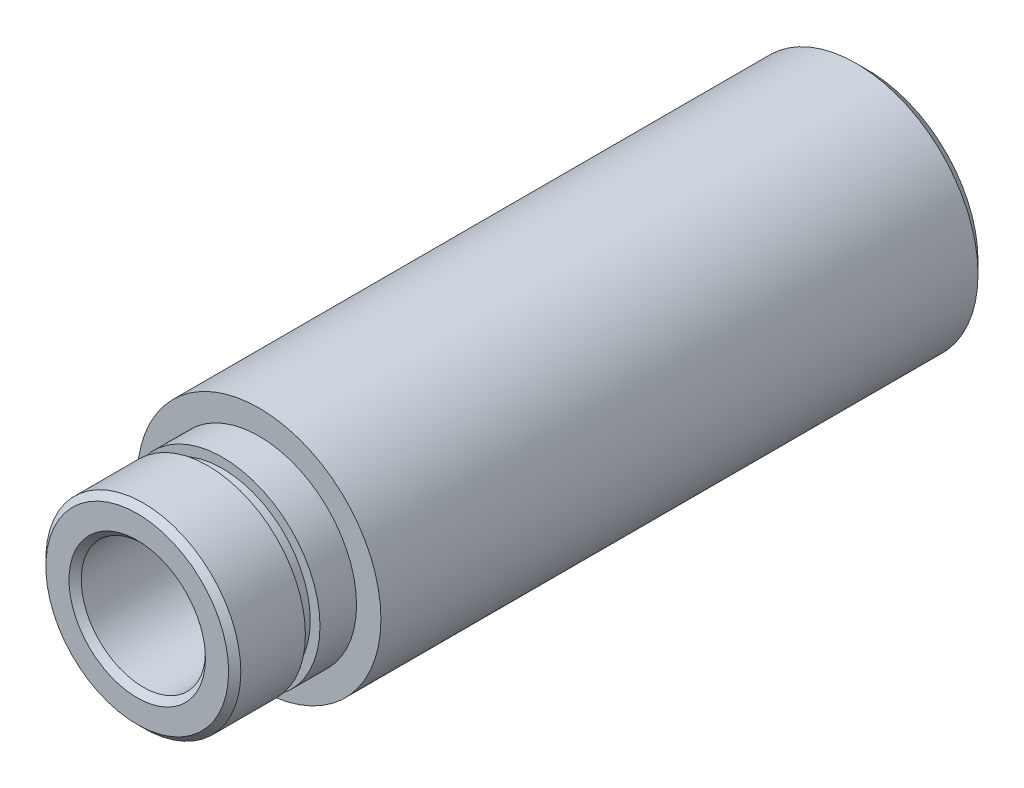
SolidWorks part; units mm, degrees
ref_plane "Alzado" through (0, 0, 0) normal (0, 0, 1) x (1, 0, 0)
ref_plane "Planta" through (0, 0, 0) normal (0, 1, 0) x (1, 0, 0)
ref_plane "Vista lateral" through (0, 0, 0) normal (1, 0, 0) x (0, 0, -1)
sketch "Croquis1" plane through (0, 0, 0) normal (0, 0, 1) x (1, 0, 0)
  circle A0 centre (0, 0) radius 5.1
  circle A1 centre (0, 0) radius 10
  dimension "D1" = 10.2
  dimension "D2" = 20
extrude "Saliente-Extruir1" add sketch "Croquis1" along normal mid plane 60
sketch "Croquis2" plane through (0, 0, 30) normal (0, 0, 1) x (1, 0, 0)
  circle A0 centre (0, 0) radius 8
  dimension "D1" = 16
extrude "Cortar-Extruir1" cut sketch "Croquis2" against normal blind 10 flip side to cut
chamfer "Chaflán1" distance 0.5 angle 45 3 edges at (5.1, 0, -30) (5.1, 0, 30) (8, 0, 30)
sketch "Croquis3" plane through (0, 0, 0) normal (0, 1, 0) x (1, 0, 0)
  line L0 (-10, -20) -> (10, -20) construction
  line L1 (13.2, -23) -> (7.2, -23)
  line L2 (13.2, -23) -> (13.2, -24.2)
  line L3 (13.2, -24.2) -> (7.2, -24.2)
  line L4 (7.2, -23) -> (7.2, -24.2)
  line L5 (0, 0) -> (0, -30) construction
  line L6 (-7.5, -30) -> (7.5, -30) construction
  dimension "D1" = 1.2
  dimension "D2" = 7.2
  dimension "D3" = 3
  dimension "D4" = 6
revolve "Cortar-Revolución1" cut sketch "Croquis3" angle 360 about L5
chamfer "Chaflán2" distance 1 angle 45 1 edges at (10, 0, -30)
